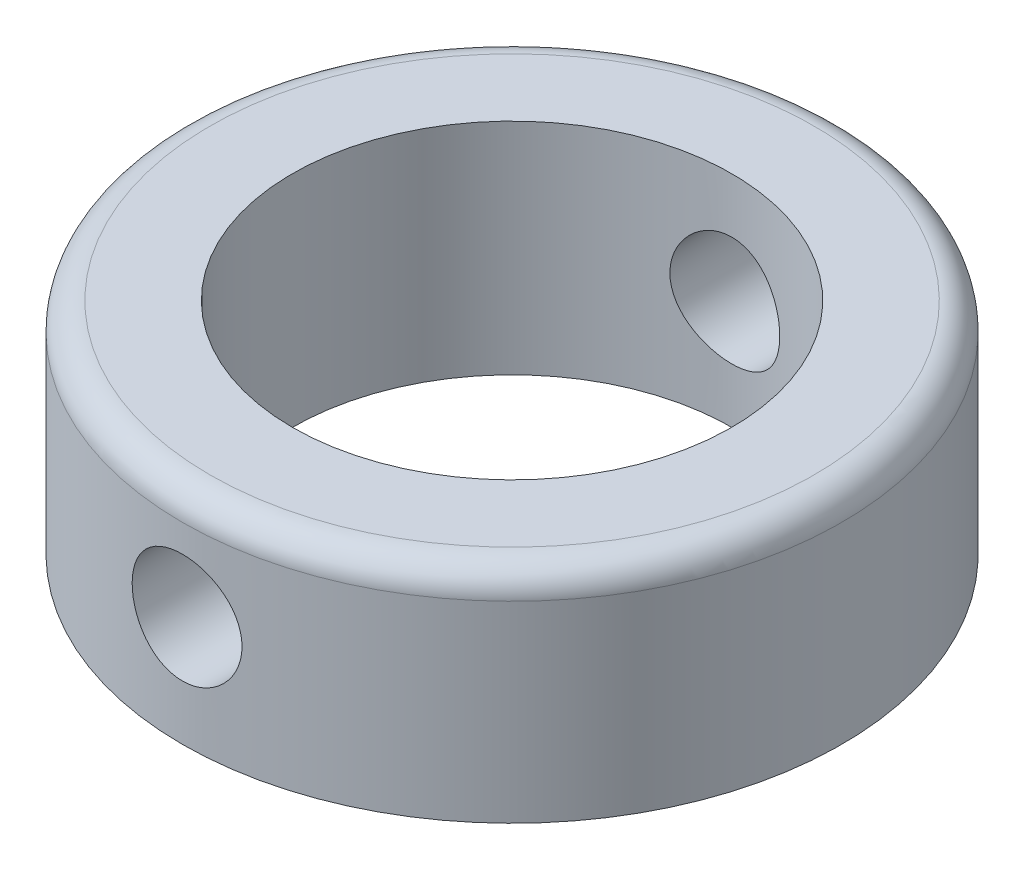
SolidWorks part; units mm, degrees
ref_plane "Front Plane" through (0, 0, 0) normal (0, 0, 1) x (1, 0, 0)
ref_plane "Top Plane" through (0, 0, 0) normal (0, 1, 0) x (1, 0, 0)
ref_plane "Right Plane" through (0, 0, 0) normal (1, 0, 0) x (0, 0, -1)
sketch "Sketch1" plane through (0, 0, 0) normal (0, 1, 0) x (1, 0, 0)
  circle A0 centre (0, 0) radius 12
  circle A1 centre (0, 0) radius 8
  dimension "D1" = 24
  dimension "D2" = 16
extrude "Boss-Extrude1" add sketch "Sketch1" along normal blind 8
sketch "Sketch2" plane through (0, 0, 0) normal (0, 0, 1) x (1, 0, 0)
  circle A0 centre (0, 4) radius 2
  dimension "D1" = 4
  dimension "D2" = 4
extrude "Cut-Extrude1" cut sketch "Sketch2" against normal mid plane 42
fillet "Fillet1" radius 1 1 edges at (0, 8, 12)
